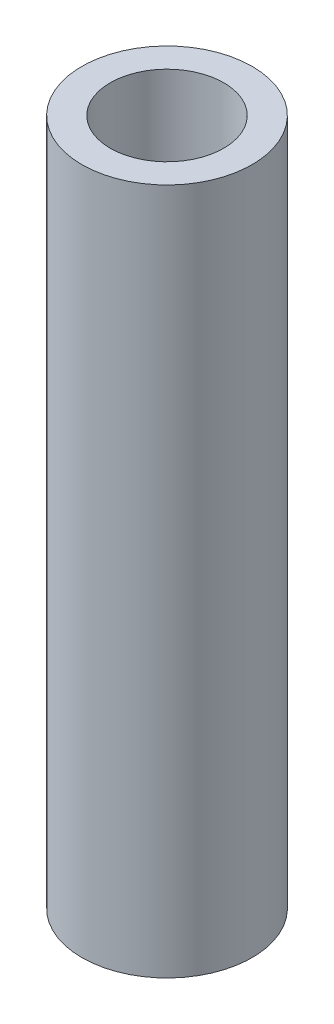
SolidWorks part; units mm, degrees
ref_plane "前视基准面" through (0, 0, 0) normal (0, 0, 1) x (1, 0, 0)
ref_plane "上视基准面" through (0, 0, 0) normal (0, 1, 0) x (1, 0, 0)
ref_plane "右视基准面" through (0, 0, 0) normal (1, 0, 0) x (0, 0, -1)
other "Configuration Table"
sketch "草图1" plane through (0, 0, 0) normal (0, 1, 0) x (1, 0, 0)
  circle A0 centre (0, 0) radius 5
  circle A1 centre (0, 0) radius 7.5
  dimension "D1" = 10
  dimension "D2" = 15
extrude "凸台-拉伸1" add sketch "草图1" along normal blind 60.5
